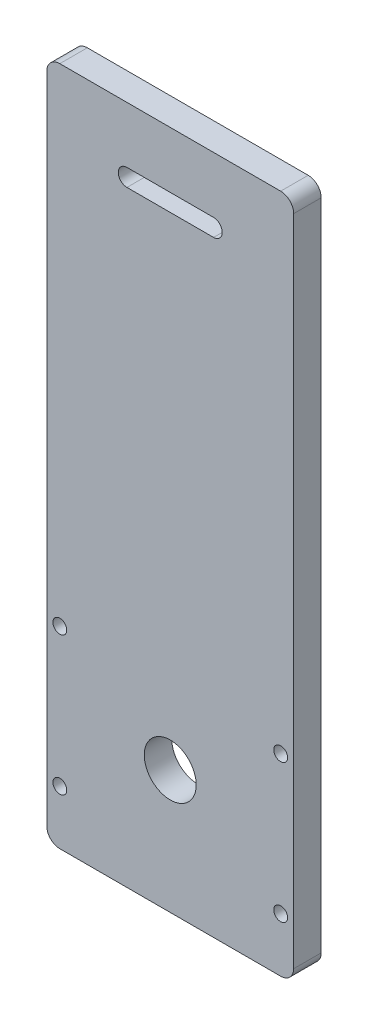
SolidWorks part; units mm, degrees
ref_plane "Front Plane" through (0, 0, 0) normal (0, 0, 1) x (1, 0, 0)
ref_plane "Top Plane" through (0, 0, 0) normal (0, 1, 0) x (1, 0, 0)
ref_plane "Right Plane" through (0, 0, 0) normal (1, 0, 0) x (0, 0, -1)
sketch "Sketch1" plane through (0, 0, 0) normal (0, 0, 1) x (1, 0, 0)
  line L1 (-28.5, 28.5) -> (28.5, 28.5)
  line L2 (-28.5, 28.5) -> (-28.5, -28.5)
  line L3 (-28.5, -28.5) -> (28.5, -28.5)
  line L4 (28.5, 28.5) -> (28.5, -28.5)
  line L5 (-28.5, 28.5) -> (28.5, -28.5) construction
  line L6 (-28.5, -28.5) -> (28.5, 28.5) construction
  line L7 (-28.5, 28.5) -> (28.5, 28.5)
  line L8 (-28.5, 28.5) -> (-28.5, 128.5)
  line L9 (-28.5, 128.5) -> (28.5, 128.5)
  line L10 (28.5, 28.5) -> (28.5, 128.5)
  circle A0 centre (0, 0) radius 6
  point P0 (0, 0)
  dimension "D4" = 12
  dimension "D1" = 57
  dimension "D2" = 57
  dimension "D3" = 100
extrude "Boss-Extrude1" add sketch "Sketch1" along normal blind 6.35 contours L1 L10 L9 L8 | L4 L1 L2 L3
sketch "Sketch3" plane through (0, 0, 6.35) normal (0, 0, 1) x (1, 0, 0)
  line L0 (-10, 113.5) -> (10, 113.5) construction
  line L1 (-10, 115.5) -> (10, 115.5)
  line L2 (-10, 111.5) -> (10, 111.5)
  line L3 (-28.5, 128.5) -> (28.5, 128.5) construction
  arc A0 (-10, 115.5) -> (-10, 111.5) centre (-10, 113.5) ccw
  arc A1 (10, 111.5) -> (10, 115.5) centre (10, 113.5) ccw
  point P2 (0, 113.5)
  dimension "D1" = 2
  dimension "D2" = 20
  dimension "D3" = 15
extrude "Cut-Extrude2" cut sketch "Sketch3" against normal through all
fillet "Fillet1" radius 3 4 edges at (-28.5, 128.5, 3.175) (28.5, 128.5, 3.175) (-28.5, -28.5, 3.175) (28.5, -28.5, 3.175)
sketch "Sketch4" plane through (0, 0, 6.35) normal (0, 0, 1) x (1, 0, 0)
  line L0 (0, 0) -> (0, -21.7943) construction
  line L1 (0, -21.7943) -> (0, 0) construction
  line L2 (0, 0) -> (38.2081, 0) construction
  circle A0 centre (25.5, -16) radius 1.6
  circle A1 centre (-25.5, -16) radius 1.6
  circle A2 centre (25.5, 16) radius 1.6
  circle A3 centre (-25.5, 16) radius 1.6
  dimension "D1" = 3.2
  dimension "D2" = 25.5
  dimension "D3" = 16
extrude "Cut-Extrude3" cut sketch "Sketch4" against normal through all
